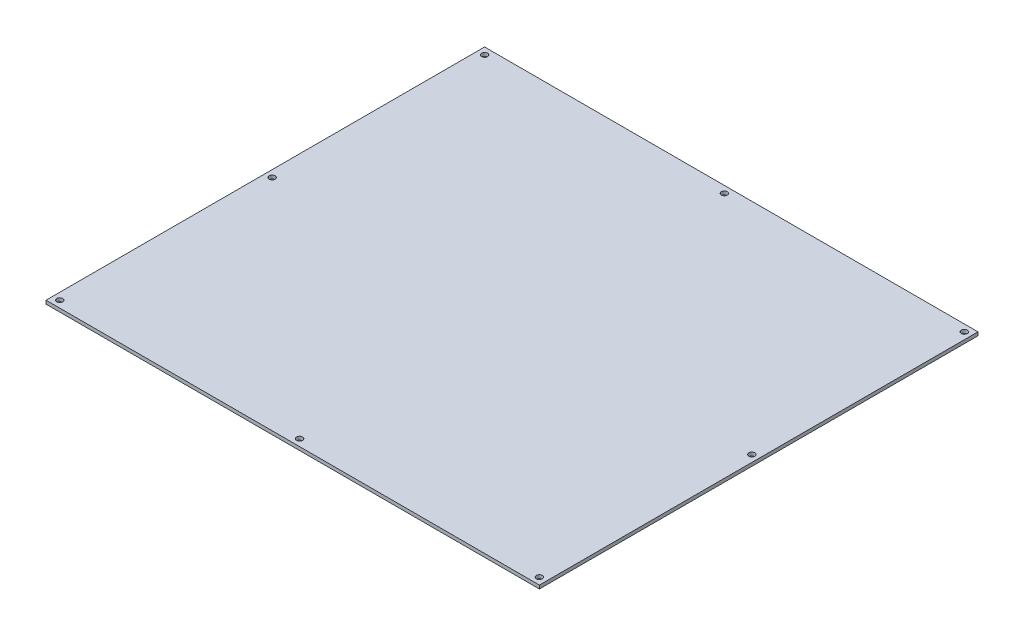
SolidWorks part; units mm, degrees
ref_plane "Front Plane" through (0, 0, 0) normal (0, 0, 1) x (1, 0, 0)
ref_plane "Top Plane" through (0, 0, 0) normal (0, 1, 0) x (1, 0, 0)
ref_plane "Right Plane" through (0, 0, 0) normal (1, 0, 0) x (0, 0, -1)
sketch "Sketch1" plane through (0, 0, 0) normal (0, 1, 0) x (1, 0, 0)
  line L1 (0, 0) -> (228.6, 0)
  line L2 (0, 0) -> (0, 203.2)
  line L3 (0, 203.2) -> (228.6, 203.2)
  line L4 (228.6, 0) -> (228.6, 203.2)
  dimension "D1" = 203.2
  dimension "D2" = 228.6
extrude "Boss-Extrude1" add sketch "Sketch1" along normal blind 1.5875
sketch "Sketch2" plane through (0, 1.5875, 0) normal (0, 1, 0) x (1, 0, 0)
  line L0 (228.6, 203.2) -> (0, 203.2) construction
  line L1 (3.175, 200.025) -> (225.425, 200.025) construction
  line L2 (3.175, 200.025) -> (3.175, 3.175) construction
  line L3 (3.175, 3.175) -> (225.425, 3.175) construction
  line L4 (225.425, 200.025) -> (225.425, 3.175) construction
  line L5 (0, 203.2) -> (0, 0) construction
  line L6 (0, 0) -> (228.6, 0) construction
  line L7 (228.6, 0) -> (228.6, 203.2) construction
  circle A0 centre (3.175, 200.025) radius 1.397
  circle A1 centre (114.3, 200.025) radius 1.397
  circle A2 centre (225.425, 200.025) radius 1.397
  circle A3 centre (3.175, 3.175) radius 1.397
  circle A4 centre (114.3, 3.175) radius 1.397
  circle A5 centre (225.425, 3.175) radius 1.397
  circle A6 centre (3.175, 101.6) radius 1.397
  circle A7 centre (225.425, 101.6) radius 1.397
  dimension "D5" = 2.794
  dimension "D1" = 3.175
  dimension "D2" = 3.175
  dimension "D3" = 3.175
  dimension "D4" = 3.175
extrude "Cut-Extrude1" cut sketch "Sketch2" against normal through all
